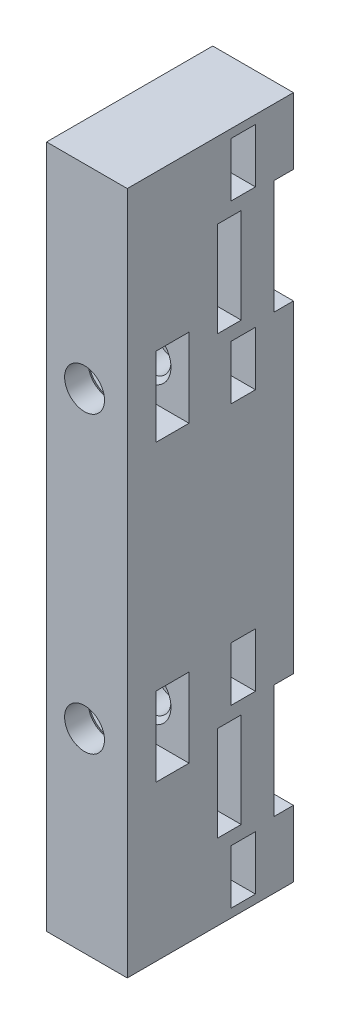
SolidWorks part; units mm, degrees
ref_plane "Plan de face" through (0, 0, 0) normal (0, 0, 1) x (1, 0, 0)
ref_plane "Plan de dessus" through (0, 0, 0) normal (0, 1, 0) x (1, 0, 0)
ref_plane "Plan de droite" through (0, 0, 0) normal (1, 0, 0) x (0, 0, -1)
sketch "Esquisse1" plane through (0, 0, 0) normal (0, 0, 1) x (1, 0, 0)
  line L0 (4, 51.5) -> (4, 20.5) construction
  line L1 (0, 0) -> (8.5, 0)
  line L2 (0, 0) -> (0, 72)
  line L3 (0, 72) -> (8.5, 72)
  line L4 (8.5, 0) -> (8.5, 72)
  circle A0 centre (4, 20.5) radius 2.1
  circle A1 centre (4, 51.5) radius 2.1
  point P9 (4, 36)
  point P10 (0, 36)
  dimension "D1" = 4.2
  dimension "D2" = 4.2
  dimension "D3" = 31
  dimension "D4" = 72
  dimension "D6" = 8.5
  dimension "D8" = 4
extrude "Boss.-Extru.1" add sketch "Esquisse1" along normal blind 17.5
sketch "Esquisse6" plane through (0, 0, 17.5) normal (0, 0, 1) x (1, 0, 0)
  line L0 (8.5, 0) -> (8.5, 72) construction
  line L1 (4, 24.6569) -> (0.4, 22.5785)
  line L2 (0.4, 22.5785) -> (0.4, 18.4215)
  line L3 (0.4, 18.4215) -> (4, 16.3431)
  line L4 (4, 16.3431) -> (7.6, 18.4215)
  line L5 (7.6, 18.4215) -> (7.6, 22.5785)
  line L6 (7.6, 22.5785) -> (4, 24.6569)
  line L7 (4, 16.3431) -> (8.5, 16.3431)
  line L8 (8.5, 16.3431) -> (8.5, 24.6569)
  line L9 (8.5, 24.6569) -> (4, 24.6569)
  circle A0 centre (4, 20.5) radius 3.6 construction
  dimension "D1" = 7.2
extrude "Enlèv. mat.-Extru.4" cut sketch "Esquisse6" against normal blind 3.5 from offset 3 offset against normal yes
sketch "Esquisse7" plane through (0, 0, 0) normal (0, 0, -1) x (-1, 0, 0)
  circle A0 centre (-4, 20.5) radius 2.1
extrude "Boss.-Extru.3" add sketch "Esquisse7" against normal blind 8
sketch "Esquisse3" plane through (0, 0, 0) normal (0, -1, 0) x (-1, 0, 0)
  line L0 (-8.5, -17.5) -> (-8.5, 0) construction
  line L1 (0, 0) -> (-8.5, 0)
  line L2 (0, 0) -> (0, -4)
  line L3 (0, -4) -> (-8.5, -4)
  line L4 (-8.5, 0) -> (-8.5, -4)
  dimension "D1" = 4
extrude "Enlèv. mat.-Extru.3" cut sketch "Esquisse3" against normal blind 19
sketch "Esquisse5" plane through (0, 0, 0) normal (0, -1, 0) x (1, 0, 0)
  line L0 (8.5, 2.0351) -> (0, 2.0351)
  line L1 (8.5, 4) -> (0, 4)
  line L2 (8.5, 4) -> (8.5, 1.7851)
  line L3 (8.5, 1.7851) -> (0, 1.7851)
  line L4 (0, 4) -> (0, 1.7851)
  line L5 (8.5, 2.7851) -> (0, 2.7851)
  line L6 (4.85, 2.0351) -> (4.85, 2.3121)
  line L7 (5.65, 2.0351) -> (5.65, 2.3121)
  circle A0 centre (5.25, 2.2301) radius 0.555
  arc A1 (5.7174, 2.5294) -> (5.8483, 2.0351) centre (4.85, 2.0351) cw
  arc A2 (4.8056, 2.5626) -> (4.6544, 2.0351) centre (5.65, 2.0351) ccw
  circle A3 centre (4.5143, 2.1851) radius 0.15
  circle A4 centre (5.9885, 2.1851) radius 0.15
  circle A5 centre (7.25, 2.2301) radius 0.555
  arc A6 (7.7174, 2.5294) -> (7.8483, 2.0351) centre (6.85, 2.0351) cw
  circle A7 centre (7.9885, 2.1851) radius 0.15
  circle A8 centre (6.5143, 2.1851) radius 0.15
  arc A9 (6.8056, 2.5626) -> (6.6544, 2.0351) centre (7.65, 2.0351) ccw
  circle A10 centre (3.25, 2.2301) radius 0.555
  arc A11 (3.7174, 2.5294) -> (3.8483, 2.0351) centre (2.85, 2.0351) cw
  circle A12 centre (3.9885, 2.1851) radius 0.15
  circle A13 centre (2.5143, 2.1851) radius 0.15
  arc A14 (2.8056, 2.5626) -> (2.6544, 2.0351) centre (3.65, 2.0351) ccw
  circle A15 centre (1.25, 2.2301) radius 0.555
  arc A16 (1.7174, 2.5294) -> (1.8483, 2.0351) centre (0.85, 2.0351) cw
  circle A17 centre (1.9885, 2.1851) radius 0.15
  circle A18 centre (0.5143, 2.1851) radius 0.15
  arc A19 (0.8056, 2.5626) -> (0.6544, 2.0351) centre (1.65, 2.0351) ccw
  circle A20 centre (-0.75, 2.2301) radius 0.555
  arc A21 (-0.2826, 2.5294) -> (-0.1517, 2.0351) centre (-1.15, 2.0351) cw
  circle A22 centre (-0.0115, 2.1851) radius 0.15
  circle A23 centre (-1.4857, 2.1851) radius 0.15
  arc A24 (-1.1944, 2.5626) -> (-1.3456, 2.0351) centre (-0.35, 2.0351) ccw
  circle A25 centre (9.25, 2.2301) radius 0.555
  circle A26 centre (8.5143, 2.1851) radius 0.15
  arc A27 (8.8056, 2.5626) -> (8.6544, 2.0351) centre (9.65, 2.0351) ccw
  arc A28 (9.7174, 2.5294) -> (9.8483, 2.0351) centre (8.85, 2.0351) cw
  circle A29 centre (9.9885, 2.1851) radius 0.15
  point P9 (4.25, 2.0351)
  point P16 (4.85, 2.1736)
  line M16 (0, 4) -> (8.5, 4)
  dimension "D2" = 1.11
  dimension "D7" = 0.3
  dimension "D8" = 0.3
  dimension "D1" = 1
  dimension "D3" = 0.75
  dimension "D4" = 0.25
  dimension "D5" = 0.4
  dimension "D6" = 0.4
  dimension "D9" = 2
  dimension "D10" = 4
  dimension "D11" = 2
extrude "Boss.-Extru.2" add sketch "Esquisse5" against normal blind 12 from offset 7 contours A26 L2 L5 A5 A6 A7 L0 | A9 A5 L5 A0 A1 A4 L0 A8 | A12 L0 A3 A2 A0 L5 A10 A11 | A17 L0 A13 A14 A10 L5 A15 A16 | A22 L4 L0 A18 A19 A15 L5 | A18 | L4 A22 | L2 A26 | A7 | A8 | A4 | A3 | A12 | L5 L2 L4 M16 | A17 | A13 offset against normal yes
sketch "Esquisse8" plane through (0, 0, 4) normal (0, 0, -1) x (-1, 0, 0)
  line L0 (-8.5, 7) -> (-8.5, 0) construction
  line L1 (0, 0) -> (-8.5, 0)
  line L2 (0, 0) -> (0, 7)
  line L3 (0, 7) -> (-8.5, 7)
  line L4 (-8.5, 0) -> (-8.5, 7)
  line L5 (0, 7) -> (-8.5, 7) construction
extrude "Boss.-Extru.4" add sketch "Esquisse8" along normal up to surface (4 mm away) up to face at (4.25, 45.5, 0)
sketch "Esquisse9" plane through (0, 0, 0) normal (0, 0, -1) x (-1, 0, 0)
  line L0 (-8.5, 0) -> (0, 0) construction
  line L1 (0, 7) -> (-8.5, 7) construction
  line L2 (0, 19) -> (-8.5, 19) construction
  circle A0 centre (-4.25, 3.75) radius 1.6
  circle A1 centre (-4.25, 22.25) radius 1.6
  point P4 (0, 0)
  point P7 (-4.25, 0)
  point P8 (0, 0)
  dimension "D1" = 3.2
  dimension "D2" = 3.2
  dimension "D3" = 3.25
  dimension "D4" = 3.25
extrude "Enlèv. mat.-Extru.5" cut sketch "Esquisse9" against normal blind 5
sketch "Esquisse10" plane through (0, 0, 0) normal (0, 0, -1) x (-1, 0, 0)
  line L0 (-5.8954, 25.1) -> (-8.5, 25.1)
  line L1 (-7.5409, 22.25) -> (-5.8954, 19.4)
  line L2 (-5.8954, 19.4) -> (-2.6046, 19.4)
  line L3 (-2.6046, 19.4) -> (-0.9591, 22.25)
  line L4 (-0.9591, 22.25) -> (-2.6046, 25.1)
  line L5 (-2.6046, 25.1) -> (-5.8954, 25.1)
  line L6 (-5.8954, 25.1) -> (-7.5409, 22.25)
  line L7 (-7.5409, 3.75) -> (-5.8954, 0.9)
  line L8 (-5.8954, 0.9) -> (-2.6046, 0.9)
  line L9 (-2.6046, 0.9) -> (-0.9591, 3.75)
  line L10 (-0.9591, 3.75) -> (-2.6046, 6.6)
  line L11 (-2.6046, 6.6) -> (-5.8954, 6.6)
  line L12 (-5.8954, 6.6) -> (-7.5409, 3.75)
  line L13 (-8.5, 19) -> (-8.5, 72) construction
  line L14 (-5.8954, 19.4) -> (-8.5, 19.4)
  line L15 (-8.5, 19.4) -> (-8.5, 25.1)
  line L16 (-5.8954, 0.9) -> (-8.5, 0.9)
  line L17 (-8.5, 0.9) -> (-8.5, 6.6)
  line L18 (-8.5, 19) -> (-8.5, 7) construction
  line L19 (-8.5, 6.6) -> (-5.8954, 6.6)
  circle A0 centre (-4.25, 22.25) radius 2.85 construction
  circle A1 centre (-4.25, 3.75) radius 2.85 construction
  circle M5 centre (-4.25, 22.25) radius 1.6
  line M9 (-8.5, 72) -> (-8.5, 19)
  dimension "D1" = 5.7
  dimension "D2" = 5.7
extrude "Enlèv. mat.-Extru.6" cut sketch "Esquisse10" against normal blind 2.6 from offset 4 contours L5 L6 L1 L2 L3 L4 M5 | L11 L12 L7 L8 L9 L10 | L19 L17 L16 L7 L12 | L14 L1 L6 L0 M9 offset against normal yes
sketch "Esquisse11" plane through (0, 0, 5) normal (0, 0, -1) x (-1, 0, 0)
  circle A0 centre (-4.25, 22.25) radius 1.6
  circle A1 centre (-4.25, 22.25) radius 1.6 construction
extrude "Enlèv. mat.-Extru.7" cut sketch "Esquisse11" against normal up to surface (1.6 mm away)
sketch "Esquisse14" plane through (8.5, 0, 0) normal (1, 0, 0) x (0, 0, -1)
  line L1 (-8, 18) -> (-5.5, 18)
  line L2 (-8, 18) -> (-8, 8)
  line L3 (-8, 8) -> (-5.5, 8)
  line L4 (-5.5, 18) -> (-5.5, 8)
  line L6 (-17.5, 0) -> (-17.5, 72) construction
  line L8 (0, 19) -> (-2.0351, 19) construction
  dimension "D1" = 2.5
  dimension "D2" = 9.5
  dimension "D3" = 10
  dimension "D4" = 1
extrude "Enlèv. mat.-Extru.9" cut sketch "Esquisse14" against normal blind 17.6
ref_plane "Plan1" through (0, 36, 0) normal (0, -1, 0) x (-1, 0, 0)
mirror "Symétrie14" about plane through (0, 36, 0) normal (0, -1, 0) of "Enlèv. mat.-Extru.9", "Enlèv. mat.-Extru.4", "Boss.-Extru.3", "Enlèv. mat.-Extru.3", "Boss.-Extru.2", "Boss.-Extru.4", "Enlèv. mat.-Extru.5", "Enlèv. mat.-Extru.6", "Enlèv. mat.-Extru.7"
chamfer "Chanfrein1" distance 0.5 angle 45 4 edges at (6.1, 20.5, 11) (6.1, 20.5, 14.5) (6.1, 51.5, 14.5) (6.1, 51.5, 11)
